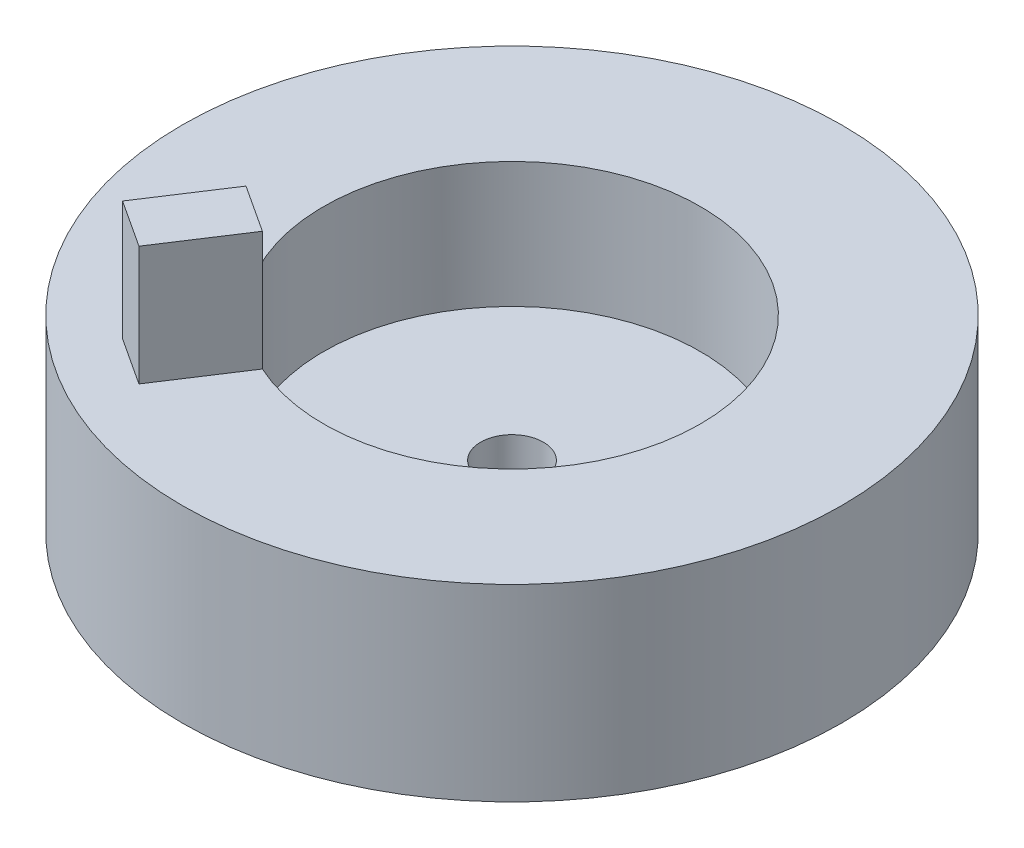
SolidWorks part; units mm, degrees
ref_plane "Front" through (0, 0, 0) normal (0, 0, 1) x (1, 0, 0)
ref_plane "Top" through (0, 0, 0) normal (0, 1, 0) x (1, 0, 0)
ref_plane "Right" through (0, 0, 0) normal (1, 0, 0) x (0, 0, -1)
sketch "Skizze1" plane through (0, 0, 0) normal (0, 1, 0) x (1, 0, 0)
  circle A0 centre (0, 0) radius 30
  circle A1 centre (0, 0) radius 52.5
  dimension "D1" = 60
  dimension "D2" = 105
extrude "Aufsatz-Linear austragen1" add sketch "Skizze1" along normal blind 20
sketch "Skizze2" plane through (0, 0, 0) normal (0, -1, 0) x (1, 0, 0)
  circle A0 centre (0, 0) radius 52.5
  circle A1 centre (0, 0) radius 5
  circle A2 centre (0, 0) radius 52.5 construction
  dimension "D1" = 10
extrude "Aufsatz-Linear austragen2" add sketch "Skizze2" along normal blind 10
sketch "Skizze3" plane through (0, 20, 0) normal (0, 1, 0) x (1, 0, 0)
  line L0 (0, 0) -> (-37.1355, -56.8406) construction
  line L5 (3.3937, 5.1945) -> (5.3998, 8.2651) construction
  line L6 (-12.4554, -27.2922) -> (-19.9899, -22.3697)
  line L7 (-19.9899, -22.3697) -> (-27.7565, -34.2575)
  line L8 (-27.7565, -34.2575) -> (-20.222, -39.18)
  line L9 (-15.7193, -24.0604) -> (-5.6769, -8.6892) construction
  line L10 (-12.4554, -27.2922) -> (-20.222, -39.18)
  circle A1 centre (0, 0) radius 30 construction
  point P16 (-23.9893, -36.7187)
  point P17 (-16.2227, -24.8309)
  dimension "D1" = 14.2
  dimension "D2" = 9
extrude "Aufsatz-Linear austragen3" add sketch "Skizze3" along normal blind 19
